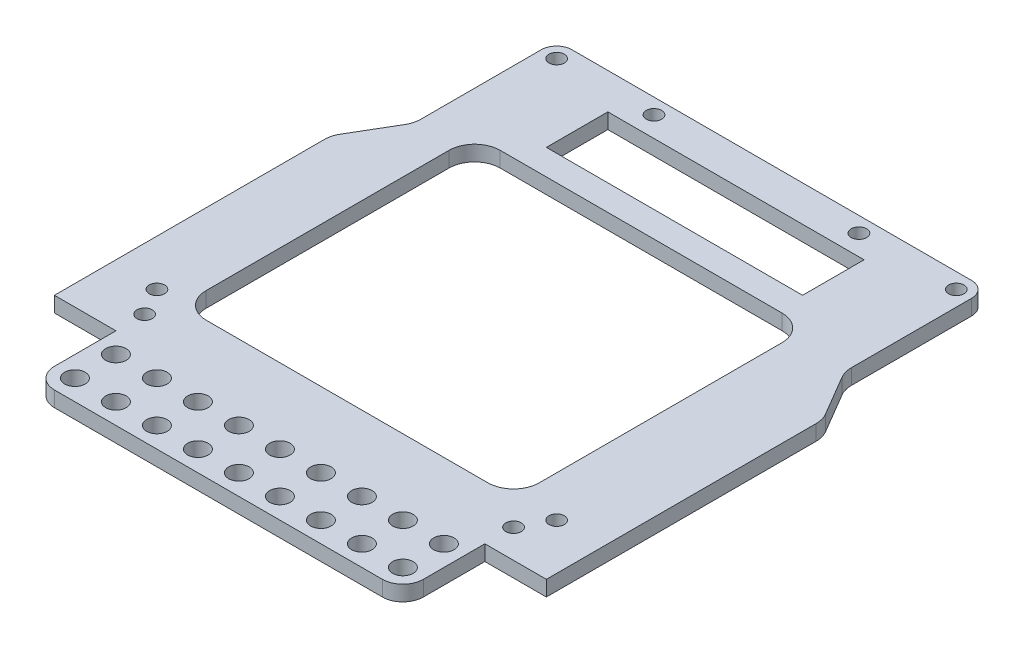
SolidWorks part; units mm, degrees
ref_plane "前基準面" through (0, 0, 0) normal (0, 0, 1) x (1, 0, 0)
ref_plane "上基準面" through (0, 0, 0) normal (0, 1, 0) x (1, 0, 0)
ref_plane "右基準面" through (0, 0, 0) normal (1, 0, 0) x (0, 0, -1)
sketch "Sketch1" plane through (0, 0, 0) normal (0, 1, 0) x (1, 0, 0)
  line L0 (43, -58) -> (48, -58) construction
  line L1 (-48, -80) -> (48, -80) construction
  line L2 (-48, -80) -> (-48, 80)
  line L3 (-48, 80) -> (48, 80)
  line L4 (48, -80) -> (48, 80)
  line L5 (0, 80) -> (0, -80) construction
  line L6 (-48, 0) -> (48, 0) construction
  line L7 (-48, -80) -> (48, -80) construction
  line L8 (-48, -80) -> (-48, -96)
  line L9 (-48, -96) -> (48, -96)
  line L10 (48, -80) -> (48, -96)
  line L11 (19.5, -31.4) -> (25.5, -31.4)
  line L12 (19.5, -31.4) -> (19.5, -59.4)
  line L13 (19.5, -59.4) -> (25.5, -59.4)
  line L14 (25.5, -31.4) -> (25.5, -59.4)
  line L15 (43, -80) -> (34.5, -80)
  line L16 (43, -80) -> (43, -31.4) construction
  line L17 (43, -31.4) -> (34.5, -31.4)
  line L18 (34.5, -80) -> (34.5, -31.4)
  line L19 (43, -31.4) -> (43.5, -31.4)
  line L20 (43, -31.4) -> (43, -58) construction
  line L21 (43, -58) -> (43.5, -58)
  line L22 (43.5, -31.4) -> (43.5, -58)
  line L23 (43, -80) -> (43, -58)
  circle A0 centre (45.5, -74) radius 1.5 construction
  circle A1 centre (45.5, -64) radius 1.5 construction
  circle A2 centre (-45.5, -64) radius 1.5 construction
  circle A3 centre (-45.5, -74) radius 1.5 construction
  circle A4 centre (45.5, -74) radius 1.5
  circle A5 centre (45.5, -64) radius 1.5
  circle A6 centre (-45.5, -64) radius 1.5
  circle A7 centre (-45.5, -74) radius 1.5
  circle A8 centre (8.25, -74) radius 1.5 construction
  circle A9 centre (8.25, -64) radius 1.5 construction
  circle A10 centre (8.25, -74) radius 1.5
  circle A11 centre (8.25, -64) radius 1.5
  circle A12 centre (15.3209, -52.5307) radius 1.65 construction
  circle A13 centre (0.2595, -52.5307) radius 1.65 construction
  circle A14 centre (15.3209, -37.4693) radius 1.65 construction
  circle A15 centre (0.2595, -37.4693) radius 1.65 construction
  circle A16 centre (15.3209, -52.5307) radius 1.65 construction
  circle A17 centre (0.2595, -52.5307) radius 1.65 construction
  circle A18 centre (15.3209, -37.4693) radius 1.65 construction
  circle A19 centre (0.2595, -37.4693) radius 1.65 construction
  circle A24 centre (0.2595, -37.4693) radius 1.65
  circle A25 centre (15.3209, -37.4693) radius 1.65
  circle A26 centre (15.3209, -52.5307) radius 1.65
  circle A27 centre (0.2595, -52.5307) radius 1.65
  circle A28 centre (17.55, -90) radius 1.5 construction
  circle A29 centre (17.55, -90) radius 1.5
  circle A30 centre (45.55, -90) radius 1.5 construction
  circle A31 centre (45.55, -90) radius 1.5
  circle A32 centre (-45.55, -90) radius 1.5
  circle A33 centre (-17.55, -90) radius 1.5
  point P0 (0, 0)
  dimension "D4" = 0.5
  dimension "D5" = 6
  dimension "D1" = 96
  dimension "D2" = 160
  dimension "D3" = 16
  dimension "D6" = 28
  dimension "D7" = 22.5
  dimension "D8" = 36.6
  dimension "D9" = 8.5
  dimension "D10" = 48.6
extrude "Boss-Extrude1" add sketch "Sketch1" along normal blind 3
sketch "Sketch3" plane through (0, 3, 0) normal (0, 1, 0) x (1, 0, 0)
  line L0 (0, -96) -> (0, 80) construction
  line L1 (-48, -96) -> (48, -96) construction
  line L2 (48, 80) -> (-48, 80) construction
  line L3 (0, 9) -> (-17.8495, 79.2684) construction
  line L4 (-17.8495, 79.2684) -> (17.8495, 79.2684) construction
  line L5 (0, 9) -> (17.8495, 79.2684) construction
  circle A0 centre (0, 9) radius 5 construction
  circle A1 centre (0, 9) radius 1.5
  circle A2 centre (-17.8495, 79.2684) radius 0.7646 construction
  circle A3 centre (17.8495, 79.2684) radius 1.5 construction
  point P12 (0, 79.2684)
  dimension "D1" = 10
  dimension "D2" = 105
  dimension "D3" = 3
  dimension "D6" = 3
  dimension "D7" = 1.5291
  dimension "D4" = 72.5
  dimension "D5" = 17.8495
extrude "Cut-Extrude2" cut sketch "Sketch3" against normal up to next
sketch "Sketch4" plane through (0, 3, 0) normal (0, 1, 0) x (1, 0, 0)
  line L0 (0, 80) -> (0, 0) construction
  line L1 (48, 80) -> (-48, 80) construction
  line L2 (48, 12) -> (25.605, 12)
  line L3 (-48, 80) -> (-25.605, 80)
  line L4 (-48, 80) -> (-48, 12)
  line L5 (-48, 12) -> (-25.605, 12)
  line L6 (-25.605, 80) -> (-25.605, 12)
  line L7 (25.605, 80) -> (25.605, 12)
  line L8 (48, 80) -> (25.605, 80)
  line L9 (48, 80) -> (48, 12)
  dimension "D1" = 51.21
  dimension "D2" = 68
extrude "Cut-Extrude3" cut sketch "Sketch4" against normal up to next
sketch "Sketch6" plane through (0, 3, 0) normal (0, 1, 0) x (1, 0, 0)
  line L0 (25.605, 80) -> (25.605, 12) construction
  line L1 (-25.605, 80) -> (25.605, 80)
  line L2 (-25.605, 80) -> (-25.605, 85)
  line L3 (-25.605, 85) -> (25.605, 85)
  line L4 (25.605, 80) -> (25.605, 85)
  dimension "D1" = 5
extrude "Boss-Extrude2" add sketch "Sketch6" against normal blind 3
sketch "Sketch7" plane through (0, 3, 0) normal (0, 1, 0) x (1, 0, 0)
  circle A0 centre (-17.8495, 79.2684) radius 1.5
  circle A1 centre (17.8495, 79.2684) radius 1.5
  dimension "D1" = 3
  dimension "D2" = 3
extrude "Cut-Extrude4" cut sketch "Sketch7" against normal up to next
sketch "Sketch9" plane through (0, 3, 0) normal (0, 1, 0) x (1, 0, 0)
  line L2 (25.605, 85) -> (-25.605, 85) construction
  line L4 (-22.6908, 44) -> (-25.605, 44) construction
  line L5 (-25.605, 12) -> (-25.605, 85) construction
  line L6 (-22.6908, 44) -> (-22.6908, 32.9821) construction
  line L7 (0, 85) -> (0, 0) construction
  circle A1 centre (-22.6908, 44) radius 1.5
  circle A2 centre (22.6908, 44) radius 1.5
  dimension "D1" = 3
  dimension "D2" = 41
extrude "Cut-Extrude5" cut sketch "Sketch9" against normal up to next
sketch "Sketch10" plane through (0, 3, 0) normal (0, 1, 0) x (1, 0, 0)
  line L0 (0, 85) -> (0, -96) construction
  line L1 (25.605, 85) -> (-25.605, 85) construction
  line L2 (-48, -96) -> (48, -96) construction
  line L3 (48, -26) -> (25.605, 12)
  line L4 (48, -96) -> (48, 12) construction
  line L5 (48, -26) -> (48, 12)
  line L6 (48, 12) -> (25.605, 12)
  line L7 (-48, -26) -> (-48, 12)
  line L8 (-48, -26) -> (-25.605, 12)
  line L9 (-48, 12) -> (-25.605, 12)
  dimension "D1" = 38
extrude "Cut-Extrude6" cut sketch "Sketch10" against normal up to next
sketch "Sketch11" plane through (0, 0, 0) normal (0, -1, 0) x (1, 0, 0)
  line L0 (-25.605, -52.6413) -> (-45.8738, -40.3515)
  line L1 (-45.8738, -40.3515) -> (-25.605, -52.6413) construction
  line L2 (-42.8854, -33.0371) -> (-31.7967, -35.6413)
  line L3 (-31.7967, -35.6413) -> (-25.605, -35.6413)
  line L4 (-16.2499, -35.6413) -> (-31.7967, -35.6413) construction
  line L5 (-25.605, -35.6413) -> (-25.605, -52.6413)
  line L6 (0, 0) -> (0, -85) construction
  line L7 (42.8854, -33.0371) -> (31.7967, -35.6413)
  line L8 (25.605, -12) -> (48, 26)
  line L9 (48, 26) -> (48, 96)
  line L10 (48, 96) -> (-48, 96)
  line L11 (-48, 96) -> (-48, 26)
  line L12 (-48, 26) -> (-25.605, -12)
  line L13 (-25.605, -12) -> (-25.605, -85)
  line L14 (-25.605, -85) -> (25.605, -85)
  line L15 (25.605, -85) -> (25.605, -12)
  line L16 (25.605, -12) -> (48, 26)
  line L17 (48, 26) -> (48, 96)
  line L18 (48, 96) -> (-48, 96)
  line L19 (-48, 96) -> (-48, 26)
  line L20 (-48, 26) -> (-25.605, -12)
  line L21 (-25.605, -12) -> (-25.605, -85)
  line L22 (-25.605, -85) -> (25.605, -85)
  line L23 (25.605, -85) -> (25.605, -12)
  line L24 (31.7967, -35.6413) -> (25.605, -35.6413)
  line L25 (25.605, -35.6413) -> (25.605, -52.6413)
  line L26 (25.605, -52.6413) -> (45.8738, -40.3515)
  arc A0 (-45.8738, -40.3515) -> (-42.8854, -33.0371) centre (-43.7999, -36.9312) cw
  circle A1 centre (-43.7999, -36.9312) radius 2.5
  circle A2 centre (-32.9303, -41.9312) radius 1.5
  circle A3 centre (32.9303, -41.9312) radius 1.5
  circle A4 centre (43.7999, -36.9312) radius 2.5
  arc A5 (45.8738, -40.3515) -> (42.8854, -33.0371) centre (43.7999, -36.9312) ccw
  line M26 (-25.605, -12) -> (-25.605, -85)
  dimension "D2" = 5
  dimension "D3" = 3
  dimension "D1" = 0
extrude "Boss-Extrude3" add sketch "Sketch11" against normal blind 3 contours A0 L0 L3 L2 A2 A1 M26 | L26 A5 L7 L24 L23 A4 A3
sketch "Sketch12" plane through (0, 0, 0) normal (0, -1, 0) x (1, 0, 0)
  line L0 (11.4001, -53.9413) -> (11.4001, -38.6413) construction
  line L1 (11.4001, -38.6413) -> (16.2501, -38.6413) construction
  line L2 (16.2501, -38.6413) -> (16.3501, -32.8413) construction
  line L3 (16.3501, -32.8413) -> (11.4001, -32.8413) construction
  line L4 (11.4001, -32.8413) -> (11.4001, -31.1913) construction
  line L5 (11.4001, -31.1913) -> (11.4001, -25.1913) construction
  line L6 (11.4001, -25.1913) -> (5.4001, -25.1913) construction
  line L7 (11.4001, -25.1913) -> (11.4001, -19.8913) construction
  line L8 (11.4001, -19.8913) -> (-2.9999, -19.8913) construction
  line L9 (-2.9999, -19.8913) -> (-2.9999, -31.1913) construction
  line L10 (-11.0999, -31.1913) -> (5.4001, -31.1913) construction
  line L11 (-2.9999, -31.1913) -> (-11.0999, -31.1913) construction
  line L12 (-11.0999, -31.1913) -> (-11.0999, -32.8413) construction
  line L13 (-11.0999, -32.8413) -> (-16.0499, -32.8413) construction
  line L14 (-16.0499, -32.8413) -> (-16.0499, -38.6413) construction
  line L15 (-15.2499, -38.6413) -> (-16.2499, -38.6413) construction
  line L16 (-16.0499, -38.6413) -> (-11.0999, -38.6413) construction
  line L17 (-11.0999, -53.9413) -> (-11.0999, -35.6413) construction
  line L18 (-11.0999, -38.6413) -> (-11.0999, -53.9413) construction
  line L19 (-11.0999, -53.9413) -> (11.4001, -53.9413) construction
  line L20 (-11.8999, -39.4413) -> (-11.8999, -54.7413)
  line L21 (-11.8999, -54.7413) -> (12.2001, -54.7413)
  line L22 (12.2001, -54.7413) -> (12.2001, -39.4413)
  line L23 (12.2001, -39.4413) -> (17.0364, -39.4413)
  line L24 (17.0364, -39.4413) -> (17.164, -32.0413)
  line L25 (17.164, -32.0413) -> (12.2001, -32.0413)
  line L26 (12.2001, -32.0413) -> (12.2001, -31.1913)
  line L27 (12.2001, -31.1913) -> (12.2001, -25.1913)
  line L28 (12.2001, -25.1913) -> (12.2001, -19.0913)
  line L29 (12.2001, -19.0913) -> (-3.7999, -19.0913)
  line L30 (-3.7999, -19.0913) -> (-3.7999, -30.3913)
  line L31 (-3.7999, -30.3913) -> (-11.8999, -30.3913)
  line L32 (-11.8999, -30.3913) -> (-11.8999, -32.0413)
  line L33 (-11.8999, -32.0413) -> (-16.8499, -32.0413)
  line L34 (-16.8499, -32.0413) -> (-16.8499, -39.4413)
  line L35 (-16.8499, -39.4413) -> (-11.8999, -39.4413)
  dimension "D2" = 16
  dimension "D3" = 11.3
  dimension "D1" = 0.8
extrude "Cut-Extrude7" cut sketch "Sketch12" against normal up to next
sketch "Sketch13" plane through (0, 0, 0) normal (0, -1, 0) x (1, 0, 0)
  line L0 (-11.8999, -39.4413) -> (-11.8999, -54.7413) construction
  line L1 (-16.8499, -29.0413) -> (-11.8999, -29.0413)
  line L2 (-16.8499, -29.0413) -> (-16.8499, -44.0413)
  line L3 (-16.8499, -44.0413) -> (-11.8999, -44.0413)
  line L4 (-11.8999, -29.0413) -> (-11.8999, -44.0413)
  line L5 (-16.8499, -32.0413) -> (-16.8499, -39.4413) construction
  line L6 (-11.8999, -32.0413) -> (-16.8499, -32.0413) construction
  line L7 (0.1501, -54.7413) -> (0.1501, -13.9321) construction
  line L8 (-11.8999, -54.7413) -> (12.2001, -54.7413) construction
  line L9 (17.1501, -29.0413) -> (17.1501, -44.0413)
  line L10 (17.1501, -29.0413) -> (12.2001, -29.0413)
  line L11 (12.2001, -29.0413) -> (12.2001, -44.0413)
  line L12 (17.1501, -44.0413) -> (12.2001, -44.0413)
  line L13 (12.2001, -54.7413) -> (12.2001, -39.4413) construction
  line L14 (12.2001, -51.376) -> (18.2789, -51.376)
  line L15 (12.2001, -51.376) -> (12.2001, -46.608)
  line L16 (12.2001, -46.608) -> (18.2789, -46.608)
  line L17 (18.2789, -51.376) -> (18.2789, -46.608)
  dimension "D1" = 3
  dimension "D2" = 15
extrude "Cut-Extrude8" cut sketch "Sketch13" against normal up to next
sketch "Sketch14" plane through (0, 0, 0) normal (0, -1, 0) x (1, 0, 0)
  line L0 (0, -85) -> (0, 0) construction
  line L1 (25.605, -85) -> (-25.605, -85) construction
  line L2 (25.605, -85) -> (25.605, -72)
  line L3 (70, -72) -> (-70, -72)
  line L4 (70, -72) -> (70, -77)
  line L5 (62, -85) -> (-62, -85)
  line L6 (-70, -72) -> (-70, -77)
  line L7 (0, -85) -> (0, -72) construction
  line L8 (70, -74.5) -> (-70, -74.5) construction
  line L9 (-25.605, -85) -> (-25.605, -72)
  arc A0 (70, -77) -> (62, -85) centre (62, -77) cw
  arc A1 (-62, -85) -> (-70, -77) centre (-62, -77) cw
  point P5 (0, -74.5)
  point P15 (70, -85)
  point P18 (-70, -85)
  dimension "D3" = 8
  dimension "D1" = 13
  dimension "D2" = 140
extrude "Boss-Extrude4" add sketch "Sketch14" against normal blind 3 contours A1 L5 L9 L3 L6 | A0 L4 L3 L2 L5
sketch "Sketch15" plane through (0, 3, 0) normal (0, 1, 0) x (1, 0, 0)
  line L0 (0, 0) -> (0, 85) construction
  line L1 (62, 85) -> (-62, 85) construction
  line L2 (20, 9) -> (-20, 9) construction
  circle A0 centre (-20, 9) radius 1.5
  circle A1 centre (20, 9) radius 1.5
  point P9 (0, 9)
  dimension "D2" = 3
  dimension "D1" = 40
extrude "Cut-Extrude9" cut sketch "Sketch15" against normal up to next
sketch "Sketch18" plane through (0, 3, 0) normal (0, 1, 0) x (1, 0, 0)
  line L0 (-25.605, 12) -> (25.605, 12)
  line L2 (83.0825, 12) -> (-87.9318, 12)
  line L3 (83.0825, 12) -> (83.0825, 92.1136)
  line L4 (83.0825, 92.1136) -> (-87.9318, 92.1136)
  line L5 (-87.9318, 12) -> (-87.9318, 92.1136)
extrude "Cut-Extrude10" cut sketch "Sketch18" against normal through all contours L5 L2 L0 L3 L4
sketch "Sketch19" plane through (0, 3, 0) normal (0, 1, 0) x (1, 0, 0)
  line L1 (43.5, -31.4) -> (34.5, -31.4)
  line L2 (43.5, -31.4) -> (43.5, -80)
  line L3 (43.5, -80) -> (34.5, -80)
  line L4 (34.5, -31.4) -> (34.5, -80)
  line L5 (25.5, -31.4) -> (-5.9684, -31.4)
  line L6 (25.5, -31.4) -> (25.5, -59.4519)
  line L7 (25.5, -59.4519) -> (-5.9684, -59.4519)
  line L8 (-5.9684, -31.4) -> (-5.9684, -59.4519)
extrude "Boss-Extrude5" add sketch "Sketch19" against normal through all
sketch "Sketch20" plane through (0, 3, 0) normal (0, 1, 0) x (1, 0, 0)
  line L0 (48, -96) -> (48, -26) construction
  line L1 (-48, -96) -> (48, -96)
  line L2 (-48, -96) -> (-48, -80)
  line L3 (-48, -80) -> (48, -80)
  line L4 (48, -96) -> (48, -80)
  dimension "D1" = 16
extrude "Cut-Extrude11" cut sketch "Sketch20" against normal through all
sketch "Sketch22" plane through (0, 3, 0) normal (0, 1, 0) x (1, 0, 0)
  line L1 (-2.0718, 7.1965) -> (2.0718, 7.1965)
  line L2 (-2.0718, 7.1965) -> (-2.0718, 10.8035)
  line L3 (-2.0718, 10.8035) -> (2.0718, 10.8035)
  line L4 (2.0718, 7.1965) -> (2.0718, 10.8035)
  line L5 (0, 10.8035) -> (0, 7.1965) construction
  line L6 (-2.0718, 9) -> (2.0718, 9) construction
  point P0 (0, 9)
extrude "Boss-Extrude6" add sketch "Sketch22" against normal through all
fillet "Fillet1" radius 5 4 edges at (-48, 1.5, 26) (-25.605, 1.5, -12) (48, 1.5, 26) (25.605, 1.5, -12)
sketch "Sketch28" plane through (0, 3, 0) normal (0, 1, 0) x (1, 0, 0)
  line L0 (0, -80) -> (0, 12) construction
  line L1 (48, -80) -> (-48, -80) construction
  line L2 (22.748, 12) -> (-22.748, 12) construction
  line L4 (25, 5) -> (-25, 5)
  line L5 (25, 5) -> (25, -7)
  line L6 (25, -7) -> (-25, -7)
  line L7 (-25, 5) -> (-25, -7)
  line L8 (0, -7) -> (0, 5) construction
  line L9 (25, -1) -> (-25, -1) construction
  point P6 (0, -1)
  dimension "D1" = 50
  dimension "D2" = 12
  dimension "D3" = 73
extrude "Cut-Extrude17" cut sketch "Sketch28" against normal through all
sketch "Sketch29" plane through (0, 0, 0) normal (0, -1, 0) x (1, 0, 0)
  line L0 (0, 80) -> (0, -12) construction
  line L1 (48, 80) -> (-48, 80) construction
  line L2 (22.748, -12) -> (-22.748, -12) construction
  line L4 (-39, -5) -> (39, -5) construction
  line L5 (-39, -5) -> (-39, 73) construction
  line L6 (-39, 73) -> (39, 73) construction
  line L7 (39, -5) -> (39, 73) construction
  line L8 (0, 73) -> (0, -5) construction
  line L9 (-39, 34) -> (39, 34) construction
  point P6 (0, 34)
  dimension "D1" = 78
  dimension "D2" = 78
sketch "Sketch30" plane through (0, 0, 0) normal (0, -1, 0) x (1, 0, 0)
  line L0 (48, 80) -> (48, 27.3637) construction
  line L1 (-48, 80) -> (48, 80)
  line L2 (-48, 80) -> (-48, 57.7477)
  line L3 (-48, 57.7477) -> (48, 57.7477)
  line L4 (48, 80) -> (48, 57.7477)
sketch "Sketch31" plane through (0, 0, 0) normal (0, -1, 0) x (1, 0, 0)
  line L0 (-48, 80) -> (48, 80) construction
  line L1 (48, 80) -> (48, 57.7477) construction
  line L2 (0, 80) -> (0, 56.0618) construction
  line L3 (0, 80) -> (0, -12) construction
  circle A0 centre (36, 74.4) radius 1.5
  circle A1 centre (-36, 74.4) radius 1.5
  dimension "D1" = 3
  dimension "D2" = 5.6
  dimension "D3" = 12
extrude "Cut-Extrude19" cut sketch "Sketch31" against normal through all
sketch "Sketch32" plane through (0, 0, 0) normal (0, -1, 0) x (1, 0, 0)
  line L0 (-48, 80) -> (48, 80) construction
  line L1 (-48, 80) -> (-42.7974, 80)
  line L2 (-48, 80) -> (-48, 58.6487)
  line L3 (-48, 58.6487) -> (-42.7974, 58.6487)
  line L4 (-42.7974, 80) -> (-42.7974, 58.6487)
  line L5 (3.9258, 80) -> (11.3912, 80)
  line L6 (3.9258, 80) -> (3.9258, 60.0646)
  line L7 (3.9258, 60.0646) -> (11.3912, 60.0646)
  line L8 (11.3912, 80) -> (11.3912, 60.0646)
  line L9 (48, 80) -> (48, 27.3637) construction
  line L10 (41.5103, 80) -> (48, 80)
  line L11 (41.5103, 80) -> (41.5103, 55.1735)
  line L12 (41.5103, 55.1735) -> (48, 55.1735)
  line L13 (48, 80) -> (48, 55.1735)
extrude "Boss-Extrude8" add sketch "Sketch32" against normal through all
sketch "Sketch34" plane through (0, 0, 0) normal (0, -1, 0) x (1, 0, 0)
  line L0 (0, 80) -> (0, -12) construction
  line L1 (48, 80) -> (-48, 80) construction
  line L2 (22.748, -12) -> (-22.748, -12) construction
  line L3 (-21.7407, -12) -> (-39, -12)
  line L4 (-39, -9) -> (39, -9) construction
  line L5 (-39, -9) -> (-39, 69) construction
  line L6 (-39, 69) -> (39, 69) construction
  line L7 (39, -9) -> (39, 69) construction
  line L8 (0, 69) -> (0, -9) construction
  line L9 (-39, 30) -> (39, 30) construction
  line L10 (-42, -9) -> (-42, 15.8192)
  line L11 (-47.3076, 24.8251) -> (-27.0556, -9.5386) construction
  line L12 (-42, 15.8192) -> (-21.7407, -12)
  line L13 (42, 15.8192) -> (21.7407, -12)
  line L14 (21.7407, -12) -> (39, -12)
  line L15 (42, -9) -> (42, 15.8192)
  circle A0 centre (-39, -9) radius 1.5
  circle A1 centre (39, -9) radius 1.5
  arc A2 (-39, -12) -> (-42, -9) centre (-39, -9) cw
  arc A3 (42, -9) -> (39, -12) centre (39, -9) cw
  circle A4 centre (-39, 69) radius 1.5
  circle A5 centre (39, 69) radius 1.5
  point P6 (0, 30)
  dimension "D4" = 3
  dimension "D5" = 3
  dimension "D6" = 3
  dimension "D7" = 3
  dimension "D8" = 3
  dimension "D1" = 78
  dimension "D2" = 78
  dimension "D3" = 3
extrude "Boss-Extrude9" add sketch "Sketch34" against normal through all
fillet "Fillet3" radius 5 2 edges at (42, 1.5, 15.8192) (-42, 1.5, 15.8192)
sketch "Sketch35" plane through (0, 3, 0) normal (0, 1, 0) x (1, 0, 0)
  line L0 (-34, 4) -> (-34, -69.4) construction
  line L1 (-39, 9) -> (36, 9) construction
  line L2 (-39, 9) -> (-39, -74.4) construction
  line L3 (-39, -74.4) -> (36, -74.4) construction
  line L4 (36, 9) -> (36, -74.4) construction
  line L5 (-29, -69.4) -> (26, -69.4)
  line L6 (31, 4) -> (31, -69.4) construction
  line L7 (-34, 4) -> (31, 4) construction
  line L8 (-29, -12) -> (26, -12)
  line L9 (-34, -17) -> (-34, -64.4)
  line L10 (31, -17) -> (31, -64.4)
  line L11 (-34, -69.4) -> (31, -69.4) construction
  arc A0 (-34, -64.4) -> (-29, -69.4) centre (-29, -64.4) ccw
  arc A1 (26, -69.4) -> (31, -64.4) centre (26, -64.4) ccw
  arc A2 (26, -12) -> (31, -17) centre (26, -17) cw
  arc A3 (-29, -12) -> (-34, -17) centre (-29, -17) ccw
  point P18 (31, -12)
  point P21 (-34, -12)
  dimension "D3" = 5
  dimension "D2" = 16
  dimension "D1" = 5
extrude "Cut-Extrude20" cut sketch "Sketch35" against normal through all
sketch "Sketch36" plane through (0, 3, 0) normal (0, 1, 0) x (1, 0, 0)
  line L0 (0, 12) -> (0, -119.8697) construction
  line L1 (39, 12) -> (-39, 12) construction
  line L2 (48, -80) -> (-48, -80) construction
  line L3 (-32, -96) -> (32, -96)
  line L4 (-36, -92) -> (-36, -80)
  line L5 (-36, -80) -> (36, -80)
  line L6 (36, -92) -> (36, -80)
  line L7 (0, -80) -> (0, -96) construction
  line L8 (-36, -86) -> (36, -86) construction
  line L9 (-32, -92) -> (-32, -80) construction
  arc A0 (32, -96) -> (36, -92) centre (32, -92) ccw
  arc A1 (-32, -96) -> (-36, -92) centre (-32, -92) cw
  circle A2 centre (-32, -92) radius 2
  circle A3 centre (-24, -92) radius 2
  circle A4 centre (-16, -92) radius 2
  circle A5 centre (-8, -92) radius 2
  circle A6 centre (0, -92) radius 2
  circle A7 centre (8, -92) radius 2
  circle A8 centre (16, -92) radius 2
  circle A9 centre (24, -92) radius 2
  circle A10 centre (32, -92) radius 2
  circle A11 centre (-32, -84) radius 2
  circle A12 centre (-24, -84) radius 2
  circle A13 centre (-16, -84) radius 2
  circle A14 centre (-8, -84) radius 2
  circle A15 centre (0, -84) radius 2
  circle A16 centre (8, -84) radius 2
  circle A17 centre (16, -84) radius 2
  circle A18 centre (24, -84) radius 2
  circle A19 centre (32, -84) radius 2
  point P5 (0, -86)
  point P13 (36, -96)
  point P17 (-36, -96)
  dimension "D3" = 4
  dimension "D4" = 4
  dimension "D6" = 8
  dimension "D1" = 72
  dimension "D2" = 16
  dimension "D5" = 9
  dimension "D7" = 9
extrude "Boss-Extrude10" add sketch "Sketch36" against normal through all
sketch "Sketch37" plane through (0, 0, 0) normal (0, -1, 0) x (1, 0, 0)
  line L1 (-39, -9) -> (39, -9) construction
  line L2 (-39, -9) -> (-39, 69) construction
  line L3 (-39, 69) -> (39, 69) construction
  line L4 (39, -9) -> (39, 69) construction
  circle A0 centre (-39, 69) radius 1.5
  circle A1 centre (39, 69) radius 1.5
  dimension "D2" = 3
  dimension "D1" = 78
extrude "Cut-Extrude21" cut sketch "Sketch37" against normal blind 10
